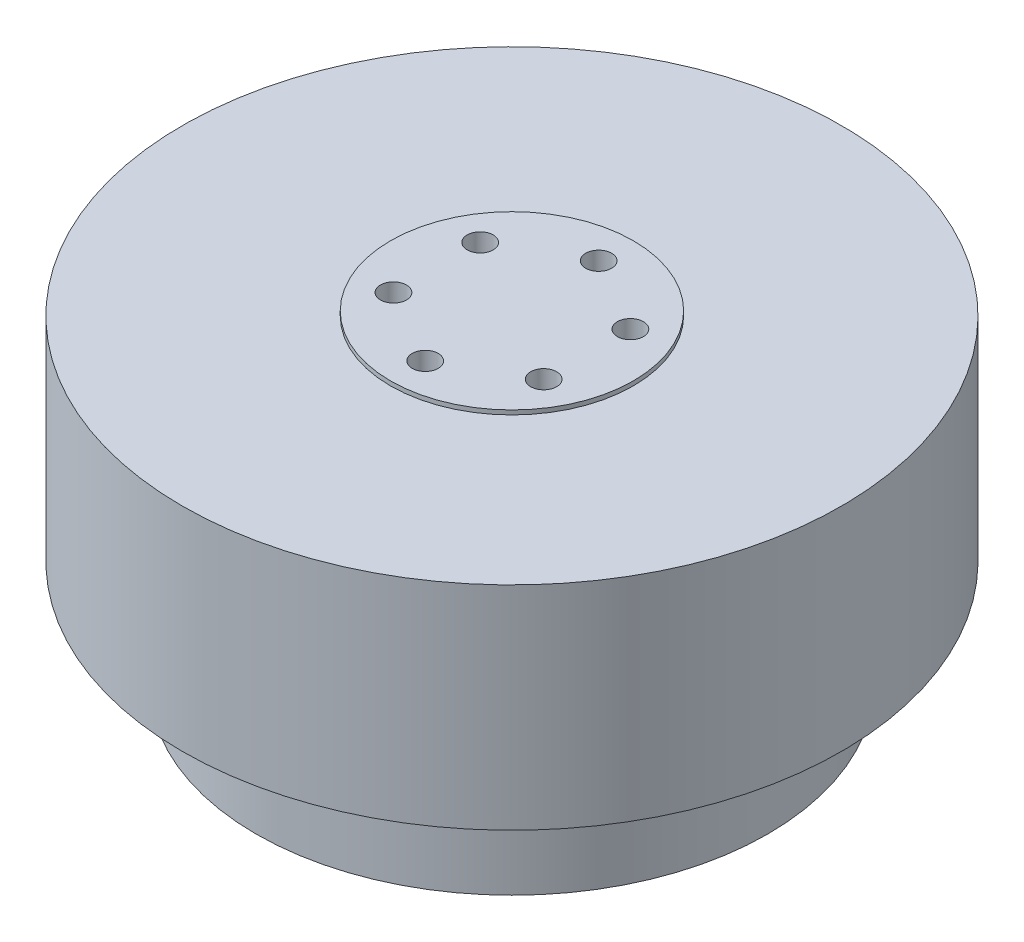
SolidWorks part; units mm, degrees
ref_plane "前视基准面" through (0, 0, 0) normal (0, 0, 1) x (1, 0, 0)
ref_plane "上视基准面" through (0, 0, 0) normal (0, 1, 0) x (1, 0, 0)
ref_plane "右视基准面" through (0, 0, 0) normal (1, 0, 0) x (0, 0, -1)
sketch "Sketch1" plane through (0, 0, 0) normal (0, 1, 0) x (1, 0, 0)
  circle A0 centre (0, 0) radius 38
  dimension "D1" = 76
extrude "Boss-Extrude1" add sketch "Sketch1" along normal blind 24.5
sketch "Sketch2" plane through (0, 24.5, 0) normal (0, 1, 0) x (1, 0, 0)
  circle A0 centre (0, 0) radius 14
  dimension "D1" = 28
extrude "Boss-Extrude2" add sketch "Sketch2" along normal blind 0.5
sketch "Sketch3" plane through (0, 0, 0) normal (0, -1, 0) x (1, 0, 0)
  circle A0 centre (0, 0) radius 29.5
  dimension "D1" = 59
extrude "Boss-Extrude3" add sketch "Sketch3" along normal blind 12.5
sketch "Sketch4" plane through (0, 25, 0) normal (0, 1, 0) x (1, 0, 0)
  circle A0 centre (0, 0) radius 10 construction
  circle A1 centre (0, 10) radius 1.5
  circle A2 centre (8.6603, 5) radius 1.5
  circle A3 centre (8.6603, -5) radius 1.5
  circle A4 centre (0, -10) radius 1.5
  circle A5 centre (-8.6603, -5) radius 1.5
  circle A6 centre (-8.6603, 5) radius 1.5
  point P17 (0, 0)
  dimension "D1" = 6
extrude "Cut-Extrude1" cut sketch "Sketch4" against normal blind 5
sketch "Sketch8" plane through (0, 0, 0) normal (0, -1, 0) x (1, 0, 0)
  circle A0 centre (0, 0) radius 34 construction
  circle A1 centre (0, 34) radius 1.5
  circle A2 centre (29.4449, 17) radius 1.5
  circle A3 centre (29.4449, -17) radius 1.5
  circle A4 centre (0, -34) radius 1.5
  circle A5 centre (-29.4449, -17) radius 1.5
  circle A6 centre (-29.4449, 17) radius 1.5
  point P17 (0, 0)
  dimension "D1" = 6
sketch "Sketch10" plane through (0, 0, 0) normal (0, -1, 0) x (1, 0, 0)
  circle A0 centre (0, 0) radius 34 construction
extrude "Cut-Extrude3" cut sketch "Sketch8" against normal blind 3
